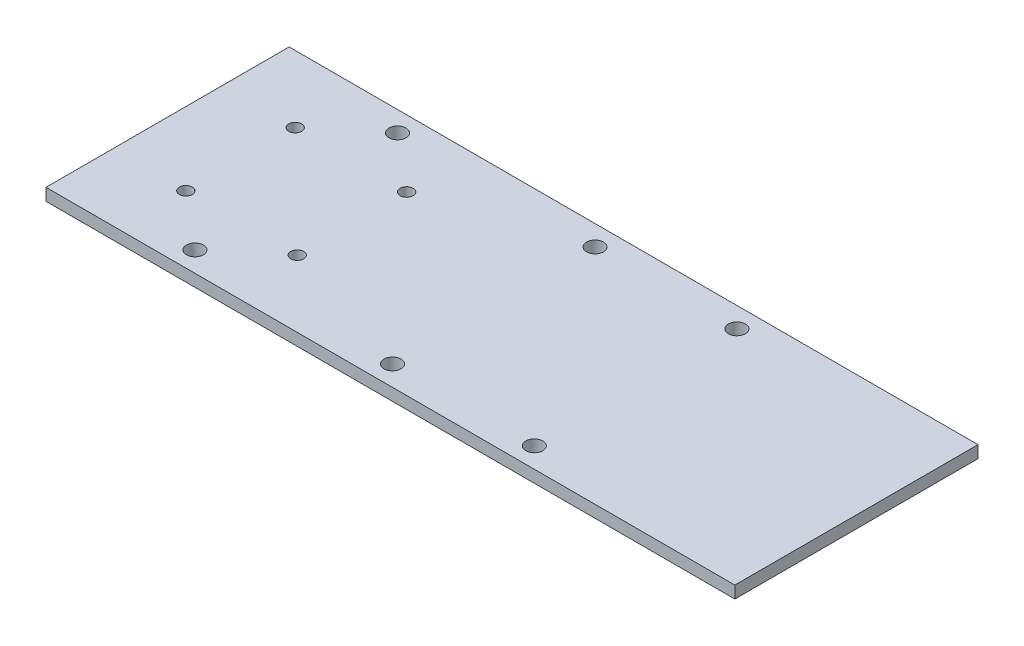
SolidWorks part; units mm, degrees
ref_plane "前视基准面" through (0, 0, 0) normal (0, 0, 1) x (1, 0, 0)
ref_plane "上视基准面" through (0, 0, 0) normal (0, 1, 0) x (1, 0, 0)
ref_plane "右视基准面" through (0, 0, 0) normal (1, 0, 0) x (0, 0, -1)
sketch "草图1" plane through (0, 0, 0) normal (0, 1, 0) x (1, 0, 0)
  line L0 (-21.4414, 42.5) -> (-21.4414, 102.5) construction
  line L1 (-246.4414, 42.5) -> (203.5586, 42.5)
  line L2 (-246.4414, 42.5) -> (-246.4414, 102.5)
  line L3 (-246.4414, 102.5) -> (203.5586, 102.5)
  line L4 (203.5586, 42.5) -> (203.5586, 102.5)
  line L5 (-61.4414, 102.5) -> (-61.4414, 168.5)
  line L6 (-61.4414, 168.5) -> (18.5586, 168.5)
  line L7 (18.5586, 168.5) -> (18.5586, 102.5)
  line L8 (-21.4414, 168.5) -> (-21.4414, 102.5) construction
  line L9 (-76.4414, 102.5) -> (-76.4414, 42.5)
  dimension "D1" = 450
  dimension "D2" = 60
  dimension "D3" = 66
  dimension "D4" = 80
  dimension "D5" = 15
extrude "凸台-拉伸1" add sketch "草图1" along normal blind 3 contours L9 L3 L2 L1
sketch "草图2" plane through (0, 3, 0) normal (0, 1, 0) x (1, 0, 0)
  line L0 (-228.4414, 59) -> (-228.4414, 86) construction
  line L1 (-200.9414, 59) -> (-200.9414, 86) construction
  line L2 (-228.4414, 86) -> (-200.9414, 86) construction
  line L3 (-130.9414, 47.5) -> (-130.9414, 97.5) construction
  line L4 (-214.6914, 86) -> (-214.6914, 102.5) construction
  line L5 (-214.6914, 97.5) -> (-165.9414, 97.5) construction
  line L6 (-246.4414, 72.5) -> (-76.4414, 72.5) construction
  line L9 (-228.4414, 72.5) -> (-130.9414, 72.5) construction
  line L11 (-76.4414, 102.5) -> (-76.4414, 42.5) construction
  line L13 (-246.4414, 42.5) -> (-246.4414, 102.5) construction
  line L14 (-246.4414, 102.5) -> (-76.4414, 102.5) construction
  circle A0 centre (-228.4414, 86) radius 1.6
  circle A1 centre (-228.4414, 59) radius 1.6
  circle A2 centre (-200.9414, 86) radius 1.6
  circle A3 centre (-200.9414, 59) radius 1.6
  circle A4 centre (-130.9414, 97.5) radius 2.1
  circle A5 centre (-165.9414, 97.5) radius 2.1
  circle A6 centre (-130.9414, 47.5) radius 2.1
  circle A7 centre (-165.9414, 47.5) radius 2.1
  circle A8 centre (-214.6914, 97.5) radius 2.1
  circle A9 centre (-214.6914, 47.5) radius 2.1
  point P3 (-228.4414, 72.5)
  point P8 (-200.9414, 72.5)
  point P13 (-130.9414, 72.5)
  point P27 (0, 0)
  point P28 (203.5586, 72.5)
  point P61 (0, 0)
  dimension "D2" = 3.2
  dimension "D6" = 70
  dimension "D7" = 45.5
  dimension "D4" = 18
  dimension "D3" = 5
  dimension "D1" = 27
extrude "切除-拉伸1" cut sketch "草图2" against normal through all
